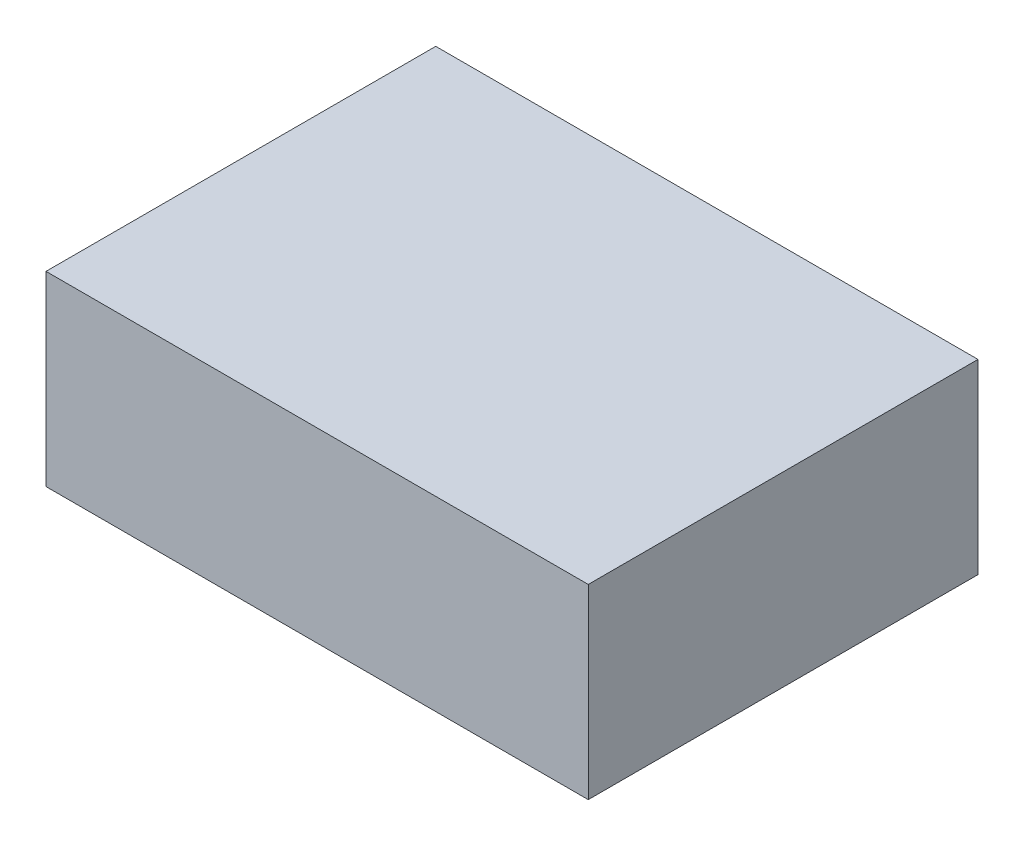
SolidWorks part; units mm, degrees
ref_plane "前视基准面" through (0, 0, 0) normal (0, 0, 1) x (1, 0, 0)
ref_plane "上视基准面" through (0, 0, 0) normal (0, 1, 0) x (1, 0, 0)
ref_plane "右视基准面" through (0, 0, 0) normal (1, 0, 0) x (0, 0, -1)
sketch "草图1" plane through (0, 0, 0) normal (0, 1, 0) x (1, 0, 0)
  line L1 (-32, -23) -> (32, -23)
  line L2 (-32, -23) -> (-32, 23)
  line L3 (-32, 23) -> (32, 23)
  line L4 (32, -23) -> (32, 23)
  line L5 (-32, -23) -> (32, 23) construction
  line L6 (-32, 23) -> (32, -23) construction
  point P0 (0, 0)
  dimension "D1" = 64
  dimension "D2" = 46
extrude "凸台-拉伸1" add sketch "草图1" along normal blind 22
